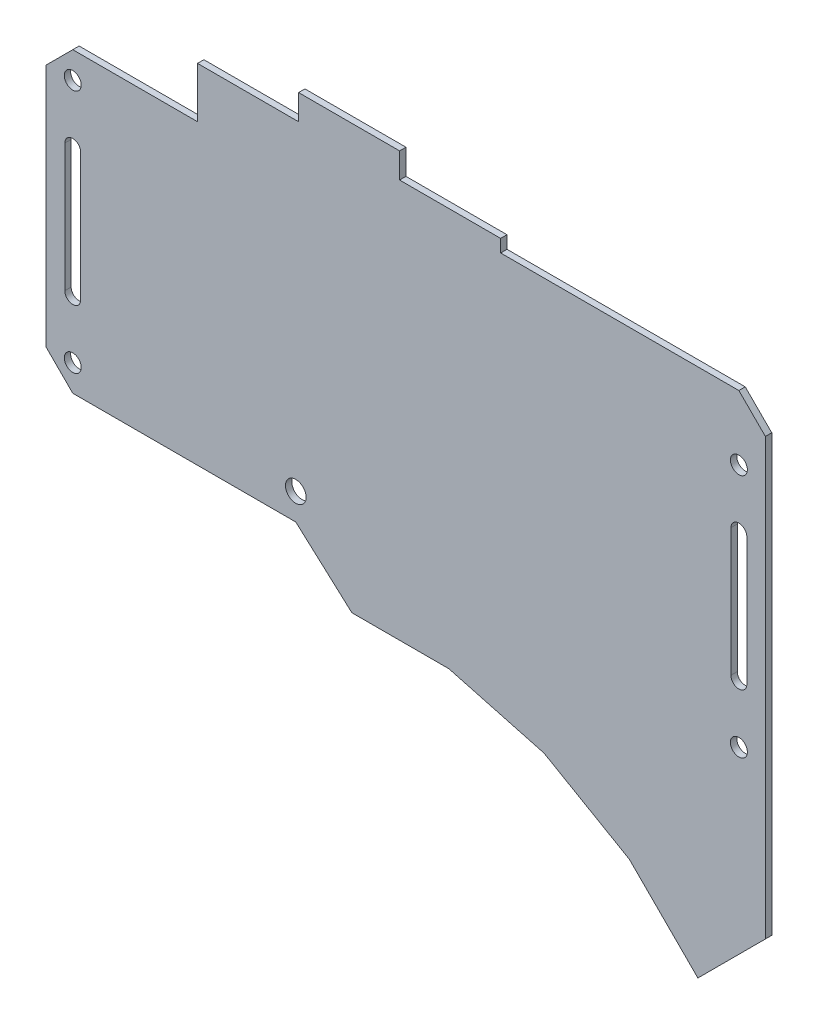
SolidWorks part; units mm, degrees
ref_plane "Plan de face" through (0, 0, 0) normal (0, 0, 1) x (1, 0, 0)
ref_plane "Plan de dessus" through (0, 0, 0) normal (0, 1, 0) x (1, 0, 0)
ref_plane "Plan de droite" through (0, 0, 0) normal (1, 0, 0) x (0, 0, -1)
sketch "Esquisse1" plane through (0, 0, 0) normal (0, 0, 1) x (1, 0, 0)
  line L0 (57.7697, 107.859) -> (75.769, 107.859) construction
  line L1 (75.769, 107.859) -> (75.769, 89.8602) construction
  line L2 (75.769, 89.8602) -> (57.7697, 89.8602) construction
  line L3 (57.7697, 89.8602) -> (57.7697, 107.859) construction
  line L4 (122.633, 13.6536) -> (132.5323, 3.7545) construction
  line L5 (132.5323, 3.7545) -> (142.4314, 13.6538) construction
  line L6 (142.4314, 13.6538) -> (132.5321, 23.5529) construction
  line L7 (132.5321, 23.5529) -> (122.633, 13.6536) construction
  line L8 (106.4982, 23.7303) -> (118.623, 16.7308) construction
  line L9 (118.623, 16.7308) -> (125.6222, 28.8552) construction
  line L10 (125.6222, 28.8552) -> (113.4975, 35.8547) construction
  line L11 (113.4975, 35.8547) -> (106.4982, 23.7303) construction
  line L12 (88.3051, 29.2895) -> (101.8291, 25.665) construction
  line L13 (101.8291, 25.665) -> (105.4531, 39.1873) construction
  line L14 (105.4531, 39.1873) -> (91.9291, 42.8117) construction
  line L15 (91.9291, 42.8117) -> (88.3051, 29.2895) construction
  line L16 (69.2947, 43.9469) -> (83.294, 43.9469) construction
  line L17 (83.294, 43.9469) -> (83.294, 29.9475) construction
  line L18 (83.294, 29.9475) -> (69.2947, 29.9475) construction
  line L19 (69.2947, 29.9475) -> (69.2947, 43.9469) construction
  line L20 (21.6697, 53.4719) -> (35.669, 53.4719) construction
  line L21 (35.669, 53.4719) -> (35.669, 39.4727) construction
  line L22 (35.669, 39.4727) -> (21.6697, 39.4727) construction
  line L23 (21.6697, 39.4727) -> (21.6697, 53.4719) construction
  line L24 (97.8697, 60.6157) -> (111.869, 60.6157) construction
  line L25 (111.869, 60.6157) -> (111.869, 46.6164) construction
  line L26 (111.869, 46.6164) -> (97.8697, 46.6164) construction
  line L27 (97.8697, 46.6164) -> (97.8697, 60.6157) construction
  line L28 (78.8197, 62.9969) -> (92.819, 62.9969) construction
  line L29 (92.819, 62.9969) -> (92.819, 48.9977) construction
  line L30 (92.819, 48.9977) -> (78.8197, 48.9977) construction
  line L31 (78.8197, 48.9977) -> (78.8197, 62.9969) construction
  line L32 (40.7197, 62.9969) -> (54.719, 62.9969) construction
  line L33 (54.719, 62.9969) -> (54.719, 48.9977) construction
  line L34 (54.719, 48.9977) -> (40.7197, 48.9977) construction
  line L35 (40.7197, 48.9977) -> (40.7197, 62.9969) construction
  line L36 (59.7697, 67.7594) -> (73.769, 67.7594) construction
  line L37 (73.769, 67.7594) -> (73.769, 53.7602) construction
  line L38 (73.769, 53.7602) -> (59.7697, 53.7602) construction
  line L39 (59.7697, 53.7602) -> (59.7697, 67.7594) construction
  line L40 (21.6697, 72.5219) -> (35.669, 72.5219) construction
  line L41 (35.669, 72.5219) -> (35.669, 58.5227) construction
  line L42 (35.669, 58.5227) -> (21.6697, 58.5227) construction
  line L43 (21.6697, 58.5227) -> (21.6697, 72.5219) construction
  line L44 (97.8697, 79.6657) -> (111.869, 79.6657) construction
  line L45 (111.869, 79.6657) -> (111.869, 65.6664) construction
  line L46 (111.869, 65.6664) -> (97.8697, 65.6664) construction
  line L47 (97.8697, 65.6664) -> (97.8697, 79.6657) construction
  line L48 (78.8197, 82.0469) -> (92.819, 82.0469) construction
  line L49 (92.819, 82.0469) -> (92.819, 68.0477) construction
  line L50 (92.819, 68.0477) -> (78.8197, 68.0477) construction
  line L51 (78.8197, 68.0477) -> (78.8197, 82.0469) construction
  line L52 (40.7197, 82.0469) -> (54.719, 82.0469) construction
  line L53 (54.719, 82.0469) -> (54.719, 68.0477) construction
  line L54 (54.719, 68.0477) -> (40.7197, 68.0477) construction
  line L55 (40.7197, 68.0477) -> (40.7197, 82.0469) construction
  line L56 (59.7697, 86.8094) -> (73.769, 86.8094) construction
  line L57 (73.769, 86.8094) -> (73.769, 72.8102) construction
  line L58 (73.769, 72.8102) -> (59.7697, 72.8102) construction
  line L59 (59.7697, 72.8102) -> (59.7697, 86.8094) construction
  line L60 (21.6697, 91.5719) -> (35.669, 91.5719) construction
  line L61 (35.669, 91.5719) -> (35.669, 77.5727) construction
  line L62 (35.669, 77.5727) -> (21.6697, 77.5727) construction
  line L63 (21.6697, 77.5727) -> (21.6697, 91.5719) construction
  line L64 (97.8697, 98.7157) -> (111.869, 98.7157) construction
  line L65 (111.869, 98.7157) -> (111.869, 84.7164) construction
  line L66 (111.869, 84.7164) -> (97.8697, 84.7164) construction
  line L67 (97.8697, 84.7164) -> (97.8697, 98.7157) construction
  line L68 (78.8197, 101.097) -> (92.819, 101.097) construction
  line L69 (92.819, 101.097) -> (92.819, 87.0977) construction
  line L70 (92.819, 87.0977) -> (78.8197, 87.0977) construction
  line L71 (78.8197, 87.0977) -> (78.8197, 101.097) construction
  line L72 (40.7197, 101.097) -> (54.719, 101.097) construction
  line L73 (54.719, 101.097) -> (54.719, 87.0977) construction
  line L74 (54.719, 87.0977) -> (40.7197, 87.0977) construction
  line L75 (40.7197, 87.0977) -> (40.7197, 101.097) construction
  line L76 (59.7697, 105.859) -> (73.769, 105.859) construction
  line L77 (73.769, 105.859) -> (73.769, 91.8602) construction
  line L78 (73.769, 91.8602) -> (59.7697, 91.8602) construction
  line L79 (59.7697, 91.8602) -> (59.7697, 105.859) construction
  line L80 (38.7197, 103.097) -> (56.719, 103.097) construction
  line L81 (56.719, 103.097) -> (56.719, 85.0977) construction
  line L82 (56.719, 85.0977) -> (38.7197, 85.0977) construction
  line L83 (38.7197, 85.0977) -> (38.7197, 103.097) construction
  line L84 (145.2598, 13.6538) -> (132.5321, 26.3813) construction
  line L85 (132.5321, 26.3813) -> (119.8046, 13.6536) construction
  line L86 (119.8046, 13.6536) -> (132.5323, 0.9261) construction
  line L87 (132.5323, 0.9261) -> (145.2598, 13.6538) construction
  line L88 (85.294, 27.9475) -> (67.2947, 27.9475) construction
  line L89 (67.2947, 27.9475) -> (67.2947, 45.9469) construction
  line L90 (67.2947, 45.9469) -> (85.294, 45.9469) construction
  line L91 (85.294, 45.9469) -> (85.294, 27.9475) construction
  line L92 (85.8556, 27.8754) -> (103.2432, 23.2155) construction
  line L93 (103.2432, 23.2155) -> (107.9026, 40.6014) construction
  line L94 (107.9026, 40.6014) -> (90.515, 45.2613) construction
  line L95 (90.515, 45.2613) -> (85.8556, 27.8754) construction
  line L96 (103.7662, 22.9981) -> (119.3552, 13.9988) construction
  line L97 (119.3552, 13.9988) -> (128.3543, 29.5874) construction
  line L98 (128.3543, 29.5874) -> (112.7653, 38.5867) construction
  line L99 (112.7653, 38.5867) -> (103.7662, 22.9981) construction
  line L100 (37.669, 37.4727) -> (19.6697, 37.4727) construction
  line L101 (19.6697, 37.4727) -> (19.6697, 55.4719) construction
  line L102 (19.6697, 55.4719) -> (37.669, 55.4719) construction
  line L103 (37.669, 55.4719) -> (37.669, 37.4727) construction
  line L104 (19.6697, 93.5719) -> (37.669, 93.5719) construction
  line L105 (37.669, 93.5719) -> (37.669, 75.5727) construction
  line L106 (37.669, 75.5727) -> (19.6697, 75.5727) construction
  line L107 (19.6697, 75.5727) -> (19.6697, 93.5719) construction
  line L108 (95.8697, 100.7157) -> (113.869, 100.7157) construction
  line L109 (113.869, 100.7157) -> (113.869, 82.7164) construction
  line L110 (113.869, 82.7164) -> (95.8697, 82.7164) construction
  line L111 (95.8697, 82.7164) -> (95.8697, 100.7157) construction
  line L112 (145.2598, 13.6538) -> (145.2598, 95.7157)
  line L113 (76.8197, 103.097) -> (94.819, 103.097) construction
  line L114 (94.819, 103.097) -> (94.819, 85.0977) construction
  line L115 (94.819, 85.0977) -> (76.8197, 85.0977) construction
  line L116 (76.8197, 85.0977) -> (76.8197, 103.097) construction
  line L117 (95.8697, 100.7157) -> (94.819, 100.7157) construction
  line L118 (76.8197, 103.097) -> (75.769, 103.097) construction
  line L119 (56.719, 103.097) -> (57.7697, 103.097) construction
  line L120 (37.669, 93.5719) -> (38.7197, 93.5719) construction
  line L121 (140.2598, 100.7157) -> (95.3443, 100.7157)
  line L122 (95.3443, 100.7157) -> (95.3443, 103.097)
  line L123 (95.3443, 103.097) -> (76.2943, 103.097)
  line L124 (76.2943, 103.097) -> (76.2943, 107.859)
  line L125 (57.2443, 103.097) -> (57.2443, 107.859)
  line L126 (57.2443, 107.859) -> (76.2943, 107.859)
  line L127 (38.1944, 93.5719) -> (38.1944, 103.097)
  line L128 (38.1944, 103.097) -> (57.2443, 103.097)
  line L129 (145.2598, 95.7157) -> (140.2598, 100.7157)
  line L130 (145.2598, 13.6538) -> (132.5323, 0.9261)
  line L131 (132.5323, 0.9261) -> (119.8046, 13.6536)
  line L132 (119.8046, 13.6536) -> (119.3552, 13.9988)
  line L133 (119.3552, 13.9988) -> (103.7662, 22.9981)
  line L134 (103.7662, 22.9981) -> (103.2432, 23.2155)
  line L135 (103.2432, 23.2155) -> (85.8556, 27.8754)
  line L136 (85.8556, 27.8754) -> (85.294, 27.9475)
  line L137 (85.294, 27.9475) -> (67.2947, 27.9475)
  line L139 (38.1944, 93.5719) -> (14.6697, 93.5719)
  line L140 (9.6697, 88.5719) -> (9.6697, 42.4727)
  line L142 (14.6697, 93.5719) -> (9.6697, 88.5719)
  line L144 (14.6697, 37.4727) -> (56.719, 37.4727)
  line L145 (56.719, 37.4727) -> (67.2947, 27.9475)
  line L146 (9.6697, 42.4727) -> (14.6697, 37.4727)
  line L147 (14.6697, 93.5719) -> (14.6697, 37.4727) construction
  line L148 (21.6697, 77.5727) -> (14.6697, 77.5727) construction
  line L149 (21.6697, 53.4719) -> (14.6697, 53.4719) construction
  line L150 (14.6697, 77.5727) -> (14.6697, 53.4719) construction
  line L153 (140.2598, 100.7157) -> (140.2598, 18.6537) construction
  line L154 (16.1697, 77.5727) -> (16.1697, 53.4719)
  line L155 (13.1697, 77.5727) -> (13.1697, 53.4719)
  line L156 (14.6697, 77.5727) -> (140.2598, 77.5727) construction
  line L159 (9.6697, 88.5719) -> (14.6697, 88.5719) construction
  line L160 (9.6697, 42.4727) -> (14.6697, 42.4727) construction
  line L161 (14.6697, 88.5719) -> (140.2598, 88.5719) construction
  line L162 (14.6697, 42.4727) -> (140.2598, 42.4727) construction
  line L163 (56.719, 37.4727) -> (56.719, 42.4727) construction
  line L164 (14.6697, 53.4719) -> (140.2598, 53.4719) construction
  line L165 (140.2598, 77.5727) -> (140.2598, 53.4719) construction
  line L166 (141.7598, 77.5727) -> (141.7598, 53.4719)
  line L167 (138.7598, 77.5727) -> (138.7598, 53.4719)
  circle A4 centre (14.6697, 42.4727) radius 1.6
  circle A5 centre (14.6697, 88.5719) radius 1.6
  circle A6 centre (140.2598, 88.5719) radius 1.6
  circle A7 centre (140.2598, 42.4727) radius 1.6
  circle A8 centre (56.719, 42.4727) radius 1.9483
  arc A9 (16.1697, 77.5727) -> (13.1697, 77.5727) centre (14.6697, 77.5727) ccw
  arc A10 (13.1697, 53.4719) -> (16.1697, 53.4719) centre (14.6697, 53.4719) ccw
  arc A11 (141.7598, 77.5727) -> (138.7598, 77.5727) centre (140.2598, 77.5727) ccw
  arc A12 (138.7598, 53.4719) -> (141.7598, 53.4719) centre (140.2598, 53.4719) ccw
  point P113 (145.2598, 100.7157)
  point P133 (9.6697, 93.5719)
  point P135 (9.6697, 27.9475)
  point P137 (9.6697, 37.4727)
  point P139 (14.6697, 65.5223)
  point P151 (140.2598, 65.5223)
  dimension "D12" = 3.2
  dimension "D13" = 3.2
  dimension "D16" = 3.2
  dimension "D17" = 3.2
  dimension "D19" = 3.8967
  dimension "D1" = 13.9993
  dimension "D4" = 2
  dimension "D2" = 2
  dimension "D3" = 2
  dimension "D5" = 2
  dimension "D6" = 2
  dimension "D7" = 2
  dimension "D8" = 2
  dimension "D9" = 2
  dimension "D10" = 2
  dimension "D11" = 2
sketch "Esquisse2" plane through (0, 0, 0) normal (0, 0, 1) x (1, 0, 0)
  line L1 (38.1944, 93.5719) -> (14.6697, 93.5719)
  line L3 (57.2443, 107.859) -> (76.2943, 107.859)
  line L112 (145.2598, 13.6538) -> (145.2598, 95.7157)
  line L121 (140.2598, 100.7157) -> (95.3443, 100.7157)
  line L122 (95.3443, 100.7157) -> (95.3443, 103.097)
  line L123 (95.3443, 103.097) -> (76.2943, 103.097)
  line L124 (76.2943, 103.097) -> (76.2943, 107.859)
  line L125 (57.2443, 103.097) -> (57.2443, 107.859)
  line L127 (38.1944, 93.5719) -> (38.1944, 103.097)
  line L128 (38.1944, 103.097) -> (57.2443, 103.097)
  line L129 (145.2598, 95.7157) -> (140.2598, 100.7157)
  line L130 (145.2598, 13.6538) -> (132.5323, 0.9261)
  line L131 (132.5323, 0.9261) -> (119.6016, 13.8565)
  line L133 (119.6016, 13.8565) -> (103.5164, 23.1423)
  line L135 (103.5164, 23.1423) -> (85.5865, 27.9475)
  line L137 (85.5865, 27.9475) -> (67.2947, 27.9475)
  line L140 (9.6697, 88.5719) -> (9.6697, 42.4727)
  line L142 (14.6697, 93.5719) -> (9.6697, 88.5719)
  line L144 (14.6697, 37.4727) -> (56.719, 37.4727)
  line L145 (56.719, 37.4727) -> (67.2947, 27.9475)
  line L146 (9.6697, 42.4727) -> (14.6697, 37.4727)
  line L154 (16.1697, 77.5727) -> (16.1697, 53.4719)
  line L155 (13.1697, 77.5727) -> (13.1697, 53.4719)
  line L166 (141.7598, 77.5727) -> (141.7598, 53.4719)
  line L167 (138.7598, 77.5727) -> (138.7598, 53.4719)
  circle A4 centre (14.6697, 42.4727) radius 1.6
  circle A5 centre (14.6697, 88.5719) radius 1.6
  circle A6 centre (140.2598, 88.5719) radius 1.6
  circle A7 centre (140.2598, 42.4727) radius 1.6
  circle A8 centre (56.719, 42.4727) radius 1.9483
  arc A9 (16.1697, 77.5727) -> (13.1697, 77.5727) centre (14.6697, 77.5727) ccw
  arc A10 (13.1697, 53.4719) -> (16.1697, 53.4719) centre (14.6697, 53.4719) ccw
  arc A11 (141.7598, 77.5727) -> (138.7598, 77.5727) centre (140.2598, 77.5727) ccw
  arc A12 (138.7598, 53.4719) -> (141.7598, 53.4719) centre (140.2598, 53.4719) ccw
  point P113 (145.2598, 100.7157)
  point P133 (9.6697, 93.5719)
  point P135 (9.6697, 27.9475)
  point P137 (9.6697, 37.4727)
  point P139 (14.6697, 65.5223)
  point P151 (140.2598, 65.5223)
  dimension "D16" = 3.2
  dimension "D17" = 3.2
extrude "Boss.-Extru.1" add sketch "Esquisse2" along normal blind 1.2
